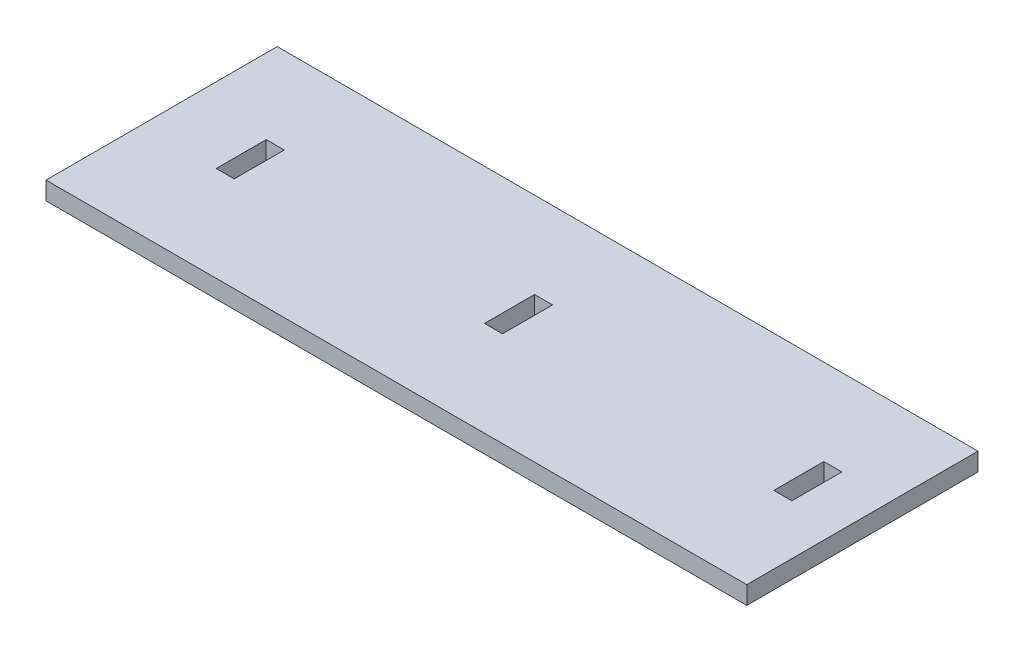
SolidWorks part; units mm, degrees
ref_plane "Front Plane" through (0, 0, 0) normal (0, 0, 1) x (1, 0, 0)
ref_plane "Top Plane" through (0, 0, 0) normal (0, 1, 0) x (1, 0, 0)
ref_plane "Right Plane" through (0, 0, 0) normal (1, 0, 0) x (0, 0, -1)
sketch "Sketch1" plane through (0, 0, 0) normal (0, 1, 0) x (1, 0, 0)
  line L1 (0, 0) -> (177.8, 0)
  line L2 (0, 0) -> (0, 58.674)
  line L3 (0, 58.674) -> (177.8, 58.674)
  line L4 (177.8, 0) -> (177.8, 58.674)
  line L5 (23.622, 24.13) -> (19.05, 24.13)
  line L6 (23.622, 24.13) -> (23.622, 36.83)
  line L7 (23.622, 36.83) -> (19.05, 36.83)
  line L8 (19.05, 24.13) -> (19.05, 36.83)
  line L9 (91.694, 24.13) -> (87.122, 24.13)
  line L10 (91.694, 24.13) -> (91.694, 36.83)
  line L11 (91.694, 36.83) -> (87.122, 36.83)
  line L12 (87.122, 24.13) -> (87.122, 36.83)
  line L13 (165.1, 24.13) -> (160.528, 24.13)
  line L14 (165.1, 24.13) -> (165.1, 36.83)
  line L15 (165.1, 36.83) -> (160.528, 36.83)
  line L16 (160.528, 24.13) -> (160.528, 36.83)
  dimension "D1" = 177.8
  dimension "D2" = 58.674
  dimension "D3" = 19.05
  dimension "D4" = 63.5
  dimension "D5" = 12.7
  dimension "D6" = 4.572
  dimension "D7" = 24.13
  dimension "D8" = 12.7
extrude "Boss-Extrude1" add sketch "Sketch1" along normal blind 4.572
